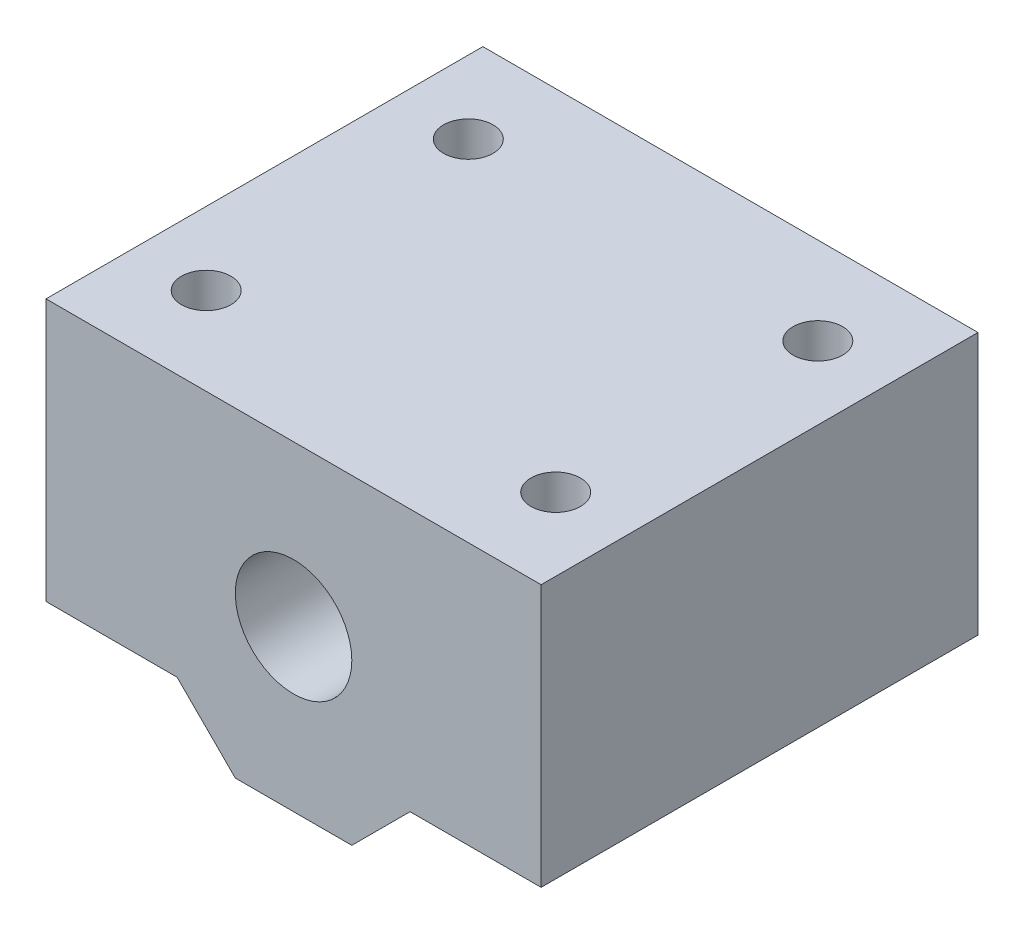
SolidWorks part; units mm, degrees
ref_plane "前视基准面" through (0, 0, 0) normal (0, 0, 1) x (1, 0, 0)
ref_plane "上视基准面" through (0, 0, 0) normal (0, 1, 0) x (1, 0, 0)
ref_plane "右视基准面" through (0, 0, 0) normal (1, 0, 0) x (0, 0, -1)
sketch "草图1" plane through (0, 0, 0) normal (0, 0, 1) x (1, 0, 0)
  line L0 (-17, -7) -> (-8, -7)
  line L1 (-4, -11) -> (4, -11)
  line L2 (-17, -7) -> (-17, 11)
  line L3 (-17, 11) -> (17, 11)
  line L4 (8, -7) -> (4, -11)
  line L5 (17, -7) -> (8, -7)
  line L6 (-8, -7) -> (-4, -11)
  line L7 (0, 11) -> (0, -11) construction
  line L8 (17, -7) -> (17, 11)
  circle A0 centre (0, 0) radius 4
  point P0 (0, 0)
  dimension "D5" = 8
  dimension "D1" = 34
  dimension "D2" = 4
  dimension "D3" = 18
  dimension "D4" = 11
extrude "凸台-拉伸1" add sketch "草图1" along normal blind 30
sketch "草图2" plane through (0, -7, 0) normal (0, -1, 0) x (1, 0, 0)
  line L1 (-17, 30) -> (-8, 30) construction
  line L2 (8, 30) -> (17, 30) construction
  circle A0 centre (-12, 24) radius 1.7
  circle A1 centre (-12, 6) radius 1.7
  circle A2 centre (12, 24) radius 1.7
  circle A3 centre (12, 6) radius 1.7
  dimension "D1" = 3.4
  dimension "D2" = 3.4
  dimension "D3" = 3.4
  dimension "D4" = 3.4
  dimension "D9" = 18
  dimension "D11" = 18
  dimension "D5" = 12
  dimension "D6" = 12
  dimension "D7" = 12
  dimension "D8" = 12
  dimension "D10" = 6
  dimension "D12" = 6
extrude "切除-拉伸1" cut sketch "草图2" against normal blind 20
